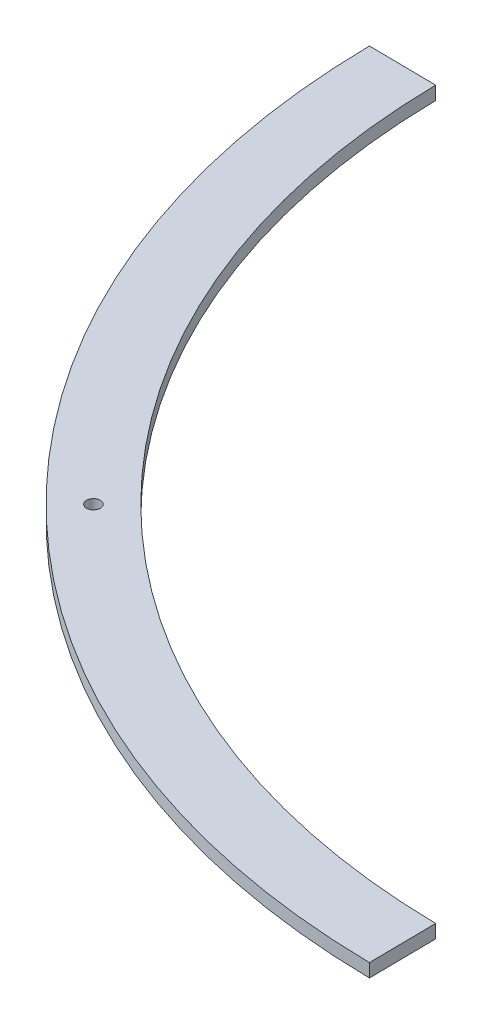
SolidWorks part; units mm, degrees
ref_plane "Front Plane" through (0, 0, 0) normal (0, 0, 1) x (1, 0, 0)
ref_plane "Top Plane" through (0, 0, 0) normal (0, 1, 0) x (1, 0, 0)
ref_plane "Right Plane" through (0, 0, 0) normal (1, 0, 0) x (0, 0, -1)
sketch "Sketch1" plane through (0, 0, 0) normal (0, 1, 0) x (1, 0, 0)
  line L0 (-90, 87.9228) -> (-74.9847, 87.75)
  line L1 (-90, -90) -> (90, -90) construction
  line L2 (-90, -90) -> (-90, 90) construction
  line L3 (-90, 90) -> (90, 90) construction
  line L4 (90, -90) -> (90, 90) construction
  line L5 (-90, -90) -> (90, 90) construction
  line L6 (-90, 90) -> (90, -90) construction
  line L15 (87.9228, -90) -> (87.7483, -74.9846)
  arc A0 (-90, 87.9228) -> (87.9228, -90) centre (90, 90) ccw
  arc A1 (-74.9847, 87.75) -> (87.7483, -74.9846) centre (90, 90) ccw
  arc A2 (-82.5, 90) -> (90, -82.5) centre (90, 90) ccw construction
  circle A6 centre (-31.9759, -31.9759) radius 1.55
  point P0 (0, 0)
  point P8 (90, -70)
  point P9 (-70, 90)
  dimension "D2" = 330
  dimension "D3" = 345
  dimension "D4" = 3.1
  dimension "D1" = 180
extrude "Boss-Extrude1" add sketch "Sketch1" along normal blind 3
